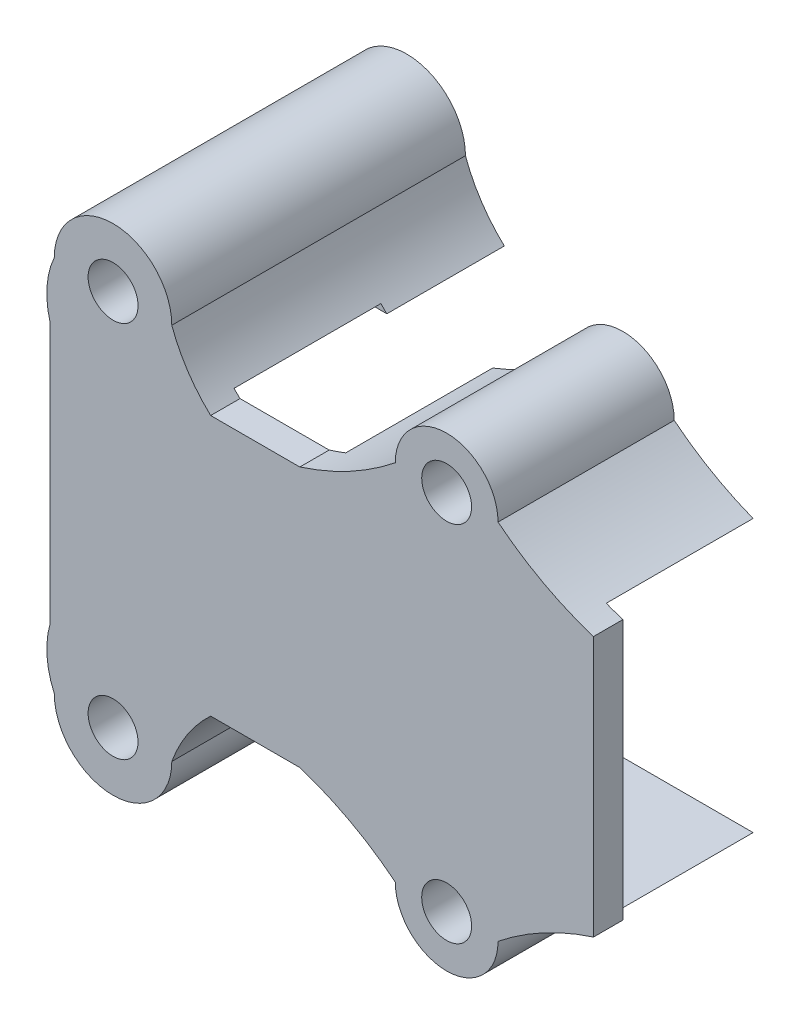
SolidWorks part; units mm, degrees
ref_plane "Alzado" through (0, 0, 0) normal (0, 0, 1) x (1, 0, 0)
ref_plane "Planta" through (0, 0, 0) normal (0, 1, 0) x (1, 0, 0)
ref_plane "Vista lateral" through (0, 0, 0) normal (1, 0, 0) x (0, 0, -1)
sketch "Croquis1" plane through (0, 0, 0) normal (0, 0, 1) x (1, 0, 0)
  line L1 (77.8857, 8.6138) -> (71.8143, 8.6138)
  line L2 (97.8857, 8.6138) -> (97.8857, -9.1138)
  line L3 (77.8857, -9.1138) -> (71.8143, -9.1138)
  line L4 (60.8857, 8.6138) -> (60.8857, -9.1138)
  line L8 (97.8857, -0.25) -> (64.7766, -0.25) construction
  arc A0 (77.8857, 8.6138) -> (84.3857, 12.1138) centre (71.6757, 27.9325) ccw construction
  arc A1 (91.3857, 12.1138) -> (97.8857, 8.6138) centre (104.0958, 27.9325) ccw construction
  arc A2 (91.3857, 12.1138) -> (84.3857, 12.1138) centre (87.8857, 12.1138) ccw construction
  arc A3 (97.8857, -9.1138) -> (91.3857, -12.6138) centre (104.0958, -28.4325) ccw construction
  arc A4 (84.3857, -12.6138) -> (77.8857, -9.1138) centre (71.6757, -28.4325) ccw construction
  arc A5 (84.3857, -12.6138) -> (91.3857, -12.6138) centre (87.8857, -12.6138) ccw construction
  arc A6 (77.8857, 8.6138) -> (84.3857, 12.1138) centre (71.6757, 27.9325) ccw
  arc A7 (91.3857, 12.1138) -> (97.8857, 8.6138) centre (104.0958, 27.9325) ccw
  arc A8 (91.3857, 12.1138) -> (84.3857, 12.1138) centre (87.8857, 12.1138) ccw
  arc A9 (97.8857, -9.1138) -> (91.3857, -12.6138) centre (104.0958, -28.4325) ccw
  arc A10 (84.3857, -12.6138) -> (77.8857, -9.1138) centre (71.6757, -28.4325) ccw
  arc A11 (84.3857, -12.6138) -> (91.3857, -12.6138) centre (87.8857, -12.6138) ccw
  circle A12 centre (65.1664, -13.1138) radius 1.7
  circle A13 centre (65.1664, 12.6138) radius 1.7
  arc A14 (69.1664, 12.6138) -> (61.1664, 12.6138) centre (65.1664, 12.6138) ccw
  arc A15 (61.1664, -13.1138) -> (69.1664, -13.1138) centre (65.1664, -13.1138) ccw
  arc A16 (60.8857, -9.1138) -> (61.1664, -13.1138) centre (66.432, -10.7345) ccw
  arc A17 (69.1664, -13.1138) -> (71.8143, -9.1138) centre (78.7468, -16.5794) cw
  arc A18 (69.1664, 12.6138) -> (71.8143, 8.6138) centre (78.7468, 16.0794) ccw
  arc A19 (60.8857, 8.6138) -> (61.1664, 12.6138) centre (66.432, 10.2345) cw
  circle A20 centre (87.8857, 12.1138) radius 1.7
  circle A21 centre (87.8857, -12.6138) radius 1.7
  dimension "D1" = 3.4
  dimension "D2" = 3.4
extrude "Saliente-Extruir1" add sketch "Croquis1" along normal blind 2
sketch "Croquis2" plane through (0, 0, 0) normal (0, 0, -1) x (-1, 0, 0)
  line L0 (-97.8857, -9.1138) -> (-77.8857, -9.1138)
  line L1 (-97.8857, 8.6138) -> (-77.8857, 8.6138)
  line L2 (-71.8143, 8.6138) -> (-60.8857, 8.6138)
  line L3 (-97.8857, -0.25) -> (-60.8857, -0.25) construction
  line L4 (-97.8857, 8.6138) -> (-97.8857, -9.1138)
  line L5 (-77.8857, -9.1138) -> (-71.8143, -9.1138)
  line L6 (-60.8857, -9.1138) -> (-60.8857, 8.6138)
  line L7 (-71.8143, 8.6138) -> (-77.8857, 8.6138)
  line L12 (-71.8143, -9.1138) -> (-60.8857, -9.1138)
  circle A0 centre (-87.8857, 12.1138) radius 1.7
  circle A1 centre (-65.1664, 12.6138) radius 1.7
  circle A2 centre (-87.8857, -12.6138) radius 1.7
  circle A3 centre (-65.1664, -13.1138) radius 1.7
  arc A12 (-97.8857, 8.6138) -> (-91.3857, 12.1138) centre (-104.0958, 27.9325) ccw
  arc A13 (-91.3857, -12.6138) -> (-97.8857, -9.1138) centre (-104.0958, -28.4325) ccw
  arc A14 (-91.3857, -12.6138) -> (-84.3857, -12.6138) centre (-87.8857, -12.6138) ccw
  arc A15 (-77.8857, -9.1138) -> (-84.3857, -12.6138) centre (-71.6757, -28.4325) ccw
  arc A16 (-69.1664, -13.1138) -> (-71.8143, -9.1138) centre (-78.7468, -16.5794) ccw
  arc A17 (-69.1664, -13.1138) -> (-61.1664, -13.1138) centre (-65.1664, -13.1138) ccw
  arc A18 (-61.1664, -13.1138) -> (-60.8857, -9.1138) centre (-66.432, -10.7345) ccw
  arc A19 (-60.8857, 8.6138) -> (-61.1664, 12.6138) centre (-66.432, 10.2345) ccw
  arc A20 (-61.1664, 12.6138) -> (-69.1664, 12.6138) centre (-65.1664, 12.6138) ccw
  arc A21 (-71.8143, 8.6138) -> (-69.1664, 12.6138) centre (-78.7468, 16.0794) ccw
  arc A22 (-84.3857, 12.1138) -> (-77.8857, 8.6138) centre (-71.6757, 27.9325) ccw
  arc A23 (-84.3857, 12.1138) -> (-91.3857, 12.1138) centre (-87.8857, 12.1138) ccw
  arc A24 (-97.8857, 8.6138) -> (-91.3857, 12.1138) centre (-104.0958, 27.9325) ccw
  arc A25 (-91.3857, -12.6138) -> (-97.8857, -9.1138) centre (-104.0958, -28.4325) ccw
  arc A26 (-91.3857, -12.6138) -> (-84.3857, -12.6138) centre (-87.8857, -12.6138) ccw
  arc A27 (-77.8857, -9.1138) -> (-84.3857, -12.6138) centre (-71.6757, -28.4325) ccw
  arc A28 (-69.1664, -13.1138) -> (-71.8143, -9.1138) centre (-78.7468, -16.5794) ccw
  arc A29 (-69.1664, -13.1138) -> (-61.1664, -13.1138) centre (-65.1664, -13.1138) ccw
  arc A30 (-61.1664, -13.1138) -> (-60.8857, -9.1138) centre (-66.432, -10.7345) ccw
  arc A31 (-60.8857, 8.6138) -> (-61.1664, 12.6138) centre (-66.432, 10.2345) ccw
  arc A32 (-61.1664, 12.6138) -> (-69.1664, 12.6138) centre (-65.1664, 12.6138) ccw
  arc A33 (-71.8143, 8.6138) -> (-69.1664, 12.6138) centre (-78.7468, 16.0794) ccw
  arc A34 (-84.3857, 12.1138) -> (-77.8857, 8.6138) centre (-71.6757, 27.9325) ccw
  arc A35 (-84.3857, 12.1138) -> (-91.3857, 12.1138) centre (-87.8857, 12.1138) ccw
  dimension "D1" = 0
extrude "Saliente-Extruir2" add sketch "Croquis2" along normal up to surface (10 mm away)
sketch "Croquis3" plane through (0, 0, -10) normal (0, 0, -1) x (-1, 0, 0)
  line L0 (-71.8143, 8.6138) -> (-60.8857, 8.6138) construction
  line L1 (-60.8857, -9.1138) -> (-71.8143, -9.1138) construction
  line L2 (-71.8143, 8.6138) -> (-60.8857, 8.6138)
  line L3 (-60.8857, -9.1138) -> (-71.8143, -9.1138)
  arc A0 (-60.8857, 8.6138) -> (-61.1664, 12.6138) centre (-66.432, 10.2345) ccw construction
  arc A1 (-61.1664, 12.6138) -> (-69.1664, 12.6138) centre (-65.1664, 12.6138) ccw construction
  arc A2 (-71.8143, 8.6138) -> (-69.1664, 12.6138) centre (-78.7468, 16.0794) ccw construction
  arc A3 (-69.1664, -13.1138) -> (-71.8143, -9.1138) centre (-78.7468, -16.5794) ccw construction
  arc A4 (-69.1664, -13.1138) -> (-61.1664, -13.1138) centre (-65.1664, -13.1138) ccw construction
  arc A5 (-61.1664, -13.1138) -> (-60.8857, -9.1138) centre (-66.432, -10.7345) ccw construction
  arc A6 (-60.8857, 8.6138) -> (-61.1664, 12.6138) centre (-66.432, 10.2345) ccw
  arc A7 (-61.1664, 12.6138) -> (-69.1664, 12.6138) centre (-65.1664, 12.6138) ccw
  arc A8 (-71.8143, 8.6138) -> (-69.1664, 12.6138) centre (-78.7468, 16.0794) ccw
  arc A9 (-69.1664, -13.1138) -> (-71.8143, -9.1138) centre (-78.7468, -16.5794) ccw
  arc A10 (-69.1664, -13.1138) -> (-61.1664, -13.1138) centre (-65.1664, -13.1138) ccw
  arc A11 (-61.1664, -13.1138) -> (-60.8857, -9.1138) centre (-66.432, -10.7345) ccw
  circle A12 centre (-65.1664, 12.6138) radius 1.7
  circle A13 centre (-65.1664, -13.1138) radius 1.7
extrude "Saliente-Extruir3" add sketch "Croquis3" along normal up to vertex
sketch "Croquis4" plane through (0, 0, -10) normal (0, 0, -1) x (-1, 0, 0)
  line L0 (-97.8857, 8.6138) -> (-77.8857, 8.6138) construction
  line L1 (-97.8857, 9.0138) -> (-60.3771, 9.0138)
  line L2 (-97.8857, 9.0138) -> (-97.8857, -9.5138)
  line L3 (-97.8857, -9.5138) -> (-60.3771, -9.5138)
  line L4 (-60.3771, 9.0138) -> (-60.3771, -9.5138)
  line L5 (-77.8857, -9.1138) -> (-97.8857, -9.1138) construction
  dimension "D1" = 0.4
  dimension "D2" = 0.4
extrude "Cortar-Extruir1" cut sketch "Croquis4" against normal up to vertex
